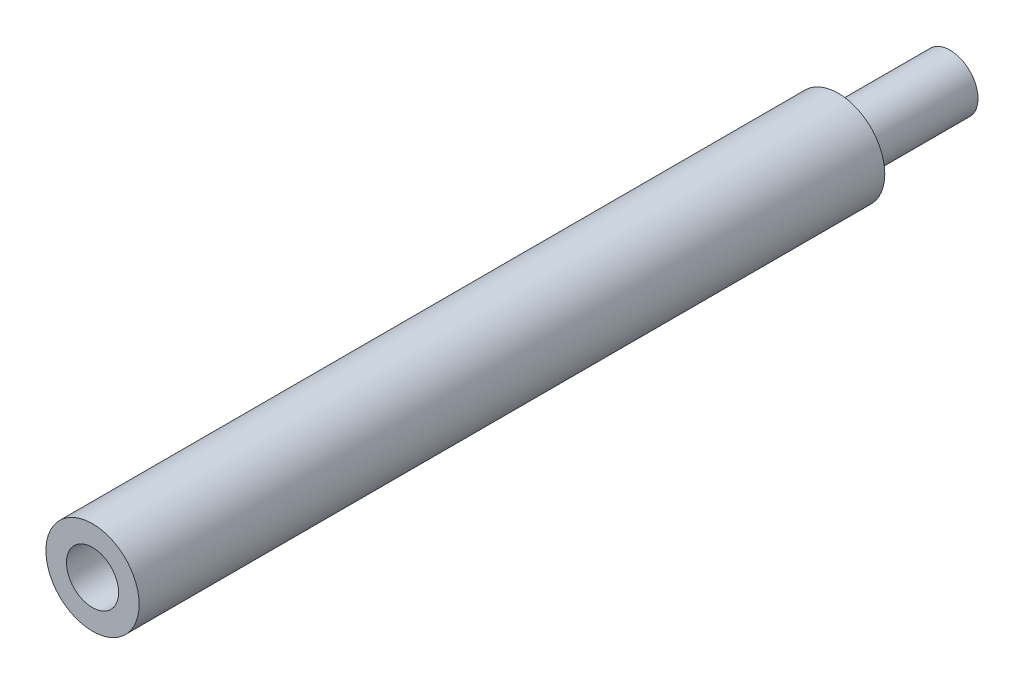
SolidWorks part; units mm, degrees
ref_plane "前视基准面" through (0, 0, 0) normal (0, 0, 1) x (1, 0, 0)
ref_plane "上视基准面" through (0, 0, 0) normal (0, 1, 0) x (1, 0, 0)
ref_plane "右视基准面" through (0, 0, 0) normal (1, 0, 0) x (0, 0, -1)
sketch "草图1" plane through (0, 0, 0) normal (0, 0, 1) x (1, 0, 0)
  circle A1 centre (0, 0) radius 1.4
  circle A2 centre (0, 0) radius 2.5
  point P2 (0, 0)
  dimension "D1" = 2.8
  dimension "D2" = 5
extrude "凸台-拉伸1" add sketch "草图1" along normal blind 40
sketch "草图2" plane through (0, 0, 0) normal (0, 0, -1) x (-1, 0, 0)
  circle A0 centre (0, 0) radius 1.5
  point P3 (0, 0)
  point P4 (0, 0)
  point P5 (0, 0)
  point P6 (-2.8653, -1.3221)
  point P7 (0, 0)
  dimension "D1" = 3
extrude "凸台-拉伸2" add sketch "草图2" along normal blind 6
